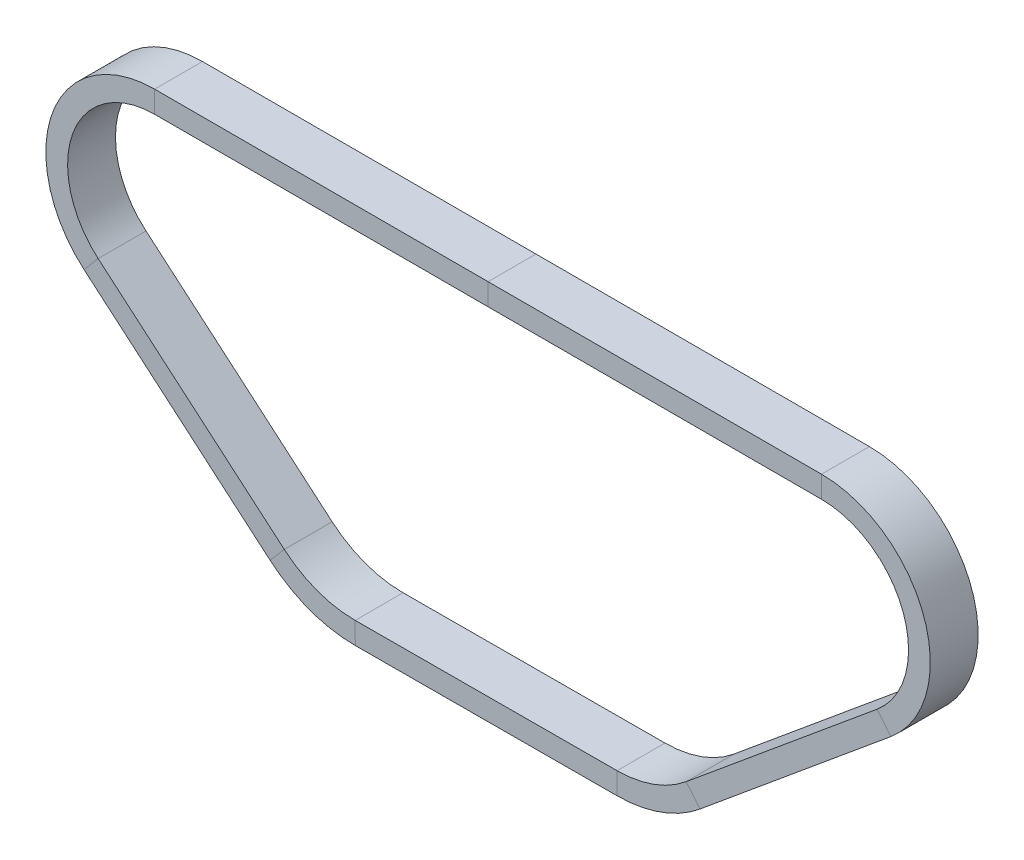
SolidWorks part; units mm, degrees
ref_plane "Front Plane" through (0, 0, 0) normal (0, 0, 1) x (1, 0, 0)
ref_plane "Top Plane" through (0, 0, 0) normal (0, 1, 0) x (1, 0, 0)
ref_plane "Right Plane" through (0, 0, 0) normal (1, 0, 0) x (0, 0, -1)
sketch "Sketch1" plane through (0, 0, 0) normal (0, 0, 1) x (1, 0, 0)
  line L0 (-912.3464, 17.2484) -> (-484.6094, -347.6412)
  line L1 (-305.2936, -413.4239) -> (296.5847, -411.5856)
  line L2 (471.2111, -348.3334) -> (909.8839, 15.178)
  line L3 (766.3206, 413.4252) -> (-766.3206, 413.4252)
  arc A0 (-766.3206, 413.4252) -> (-912.3464, 17.2484) centre (-766.3206, 188.4252) ccw
  arc A1 (-484.6094, -347.6412) -> (-305.2936, -413.4239) centre (-306.1335, -138.4252) ccw
  arc A2 (296.5847, -411.5856) -> (471.2111, -348.3334) centre (295.7448, -136.5869) ccw
  arc A3 (909.8839, 15.178) -> (766.3206, 413.4252) centre (766.3206, 188.4252) ccw
sketch "Sketch2" plane through (0, 0, 0) normal (1, 0, 0) x (0, 0, -1)
  line L0 (0, 413.4252) -> (0, 15.178) construction
  line L1 (-55, 438.4252) -> (55, 438.4252)
  line L2 (-55, 438.4252) -> (-55, 388.4252)
  line L3 (-55, 388.4252) -> (55, 388.4252)
  line L4 (55, 438.4252) -> (55, 388.4252)
  line L5 (-55, 438.4252) -> (55, 388.4252) construction
  line L6 (-55, 388.4252) -> (55, 438.4252) construction
  point P0 (0, 413.4252)
  dimension "D1" = 50
  dimension "D2" = 110
sweep "Sweep1" add profiles "Sketch2" path "Sketch1"
